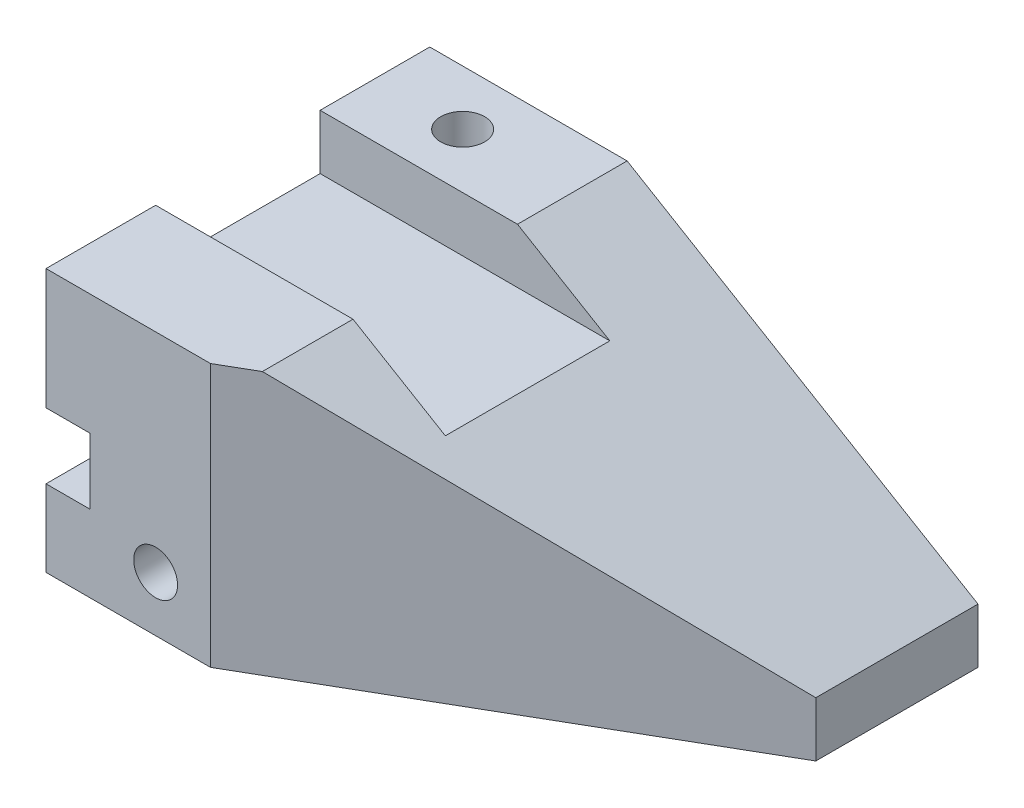
SolidWorks part; units mm, degrees
ref_plane "前视基准面" through (0, 0, 0) normal (0, 0, 1) x (1, 0, 0)
ref_plane "上视基准面" through (0, 0, 0) normal (0, 1, 0) x (1, 0, 0)
ref_plane "右视基准面" through (0, 0, 0) normal (1, 0, 0) x (0, 0, -1)
sketch "草图7" plane through (0, 0, 0) normal (0, 0, 1) x (1, 0, 0)
  line L0 (0, 0) -> (250, 0)
  line L1 (55, 0) -> (-55, 0) construction
  line L2 (250, 0) -> (250, 25)
  line L3 (250, 25) -> (90, 120)
  line L4 (90, 120) -> (0, 120)
  line L5 (0, 120) -> (0, 0)
  dimension "D1" = 250
  dimension "D2" = 120
  dimension "D3" = 90
  dimension "D4" = 25
extrude "凸台-拉伸3" add sketch "草图7" along normal blind 175
sketch "草图8" plane through (0, 0, 0) normal (0, 1, 0) x (1, 0, 0)
  line L5 (75, -175) -> (250, -73.9637)
  line L6 (0, -175) -> (250, -175) construction
  line L7 (250, -175) -> (250, 0) construction
  line L8 (250, -73.9637) -> (250, -175)
  line L9 (250, -175) -> (75, -175)
  dimension "D1" = 75
  dimension "D2" = 30
extrude "切除-拉伸2" cut sketch "草图8" along normal blind 220
sketch "草图9" plane through (0, 0, 0) normal (-1, 0, 0) x (0, 0, 1)
  line L0 (50, 120) -> (50, 95)
  line L1 (175, 120) -> (0, 120) construction
  line L2 (50, 95) -> (125, 95)
  line L3 (125, 95) -> (125, 120)
  line L4 (125, 120) -> (50, 120)
  dimension "D1" = 50
  dimension "D2" = 75
  dimension "D3" = 25
extrude "切除-拉伸3" cut sketch "草图9" against normal blind 220
sketch "草图10" plane through (0, 0, 175) normal (0, 0, 1) x (1, 0, 0)
  line L0 (0, 65) -> (20, 65)
  line L1 (0, 120) -> (0, 0) construction
  line L2 (20, 65) -> (20, 35)
  line L3 (20, 35) -> (0, 35)
  line L4 (0, 35) -> (0, 65)
  dimension "D1" = 20
  dimension "D2" = 30
  dimension "D3" = 35
extrude "切除-拉伸4" cut sketch "草图10" against normal blind 220 contours L4 L0 L2 L3
sketch "草图11" plane through (0, 0, 175) normal (0, 0, 1) x (1, 0, 0)
  line L0 (0, 0) -> (75, 0) construction
  line L1 (0, 35) -> (0, 0) construction
  circle A0 centre (50, 25) radius 10
  dimension "D1" = 25
  dimension "D3" = 20
  dimension "D2" = 50
extrude "切除-拉伸5" cut sketch "草图11" against normal blind 220 contours A0
sketch "草图12" plane through (0, 120, 0) normal (0, 1, 0) x (1, 0, 0)
  line L0 (90, 0) -> (0, 0) construction
  line L1 (0, -50) -> (0, 0) construction
  circle A0 centre (40, -25) radius 10
  point P8 (40.3181, 0)
  dimension "D1" = 25
  dimension "D3" = 20
  dimension "D2" = 40
extrude "切除-拉伸6" cut sketch "草图12" against normal blind 220
